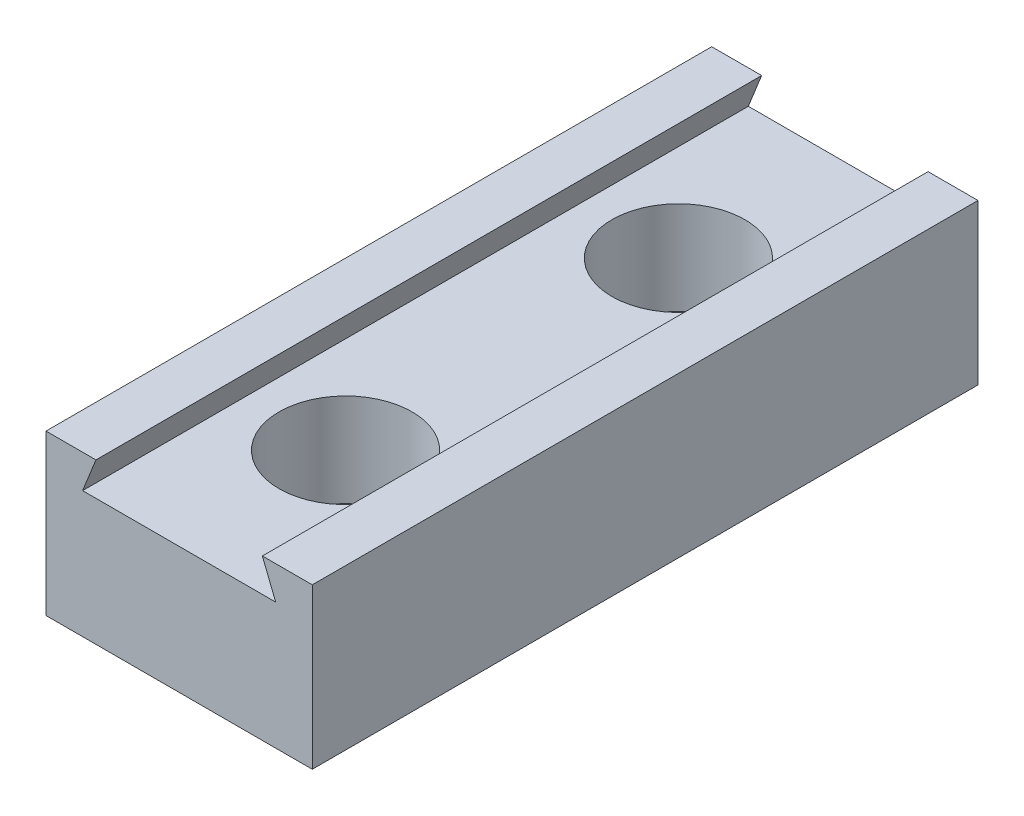
SolidWorks part; units mm, degrees
ref_plane "Front Plane" through (0, 0, 0) normal (0, 0, 1) x (1, 0, 0)
ref_plane "Top Plane" through (0, 0, 0) normal (0, 1, 0) x (1, 0, 0)
ref_plane "Right Plane" through (0, 0, 0) normal (1, 0, 0) x (0, 0, -1)
sketch "Sketch1" plane through (0, 0, 0) normal (0, 1, 0) x (1, 0, 0)
  line L1 (-10, -25) -> (10, -25)
  line L2 (-10, -25) -> (-10, 25)
  line L3 (-10, 25) -> (10, 25)
  line L4 (10, -25) -> (10, 25)
  line L5 (-10, -25) -> (10, 25) construction
  line L6 (-10, 25) -> (10, -25) construction
  point P0 (0, 0)
extrude "Boss-Extrude1" add sketch "Sketch1" along normal blind 12
sketch "Sketch2" plane through (0, 0, 25) normal (0, 0, 1) x (1, 0, 0)
  line L0 (0, 12) -> (0, 9.5) construction
  line L8 (-10, 12) -> (10, 12) construction
  line L9 (0, 9.5) -> (7.25, 9.5)
  line L10 (0, 9.5) -> (-7.25, 9.5)
  line L11 (0, 12) -> (6.25, 12)
  line L12 (0, 12) -> (-6.25, 12)
  line L13 (-7.25, 9.5) -> (-6.25, 12)
  line L14 (6.25, 12) -> (7.25, 9.5)
extrude "Cut-Extrude1" cut sketch "Sketch2" against normal up to next
sketch "Sketch3" plane through (0, 9.5, 0) normal (0, 1, 0) x (1, 0, 0)
  line L0 (0, 0) -> (0, 12.5) construction
  line L2 (0, 0) -> (0, -12.5) construction
  circle A0 centre (0, 12.5) radius 5
  circle A1 centre (0, -12.5) radius 5
extrude "Cut-Extrude3" cut sketch "Sketch3" against normal blind 7
sketch "Sketch4" plane through (0, 2.5, 0) normal (0, 1, 0) x (1, 0, 0)
  circle A0 centre (0, 12.5) radius 2.25
  circle A1 centre (0, -12.5) radius 2.25
extrude "Cut-Extrude4" cut sketch "Sketch4" against normal up to next
